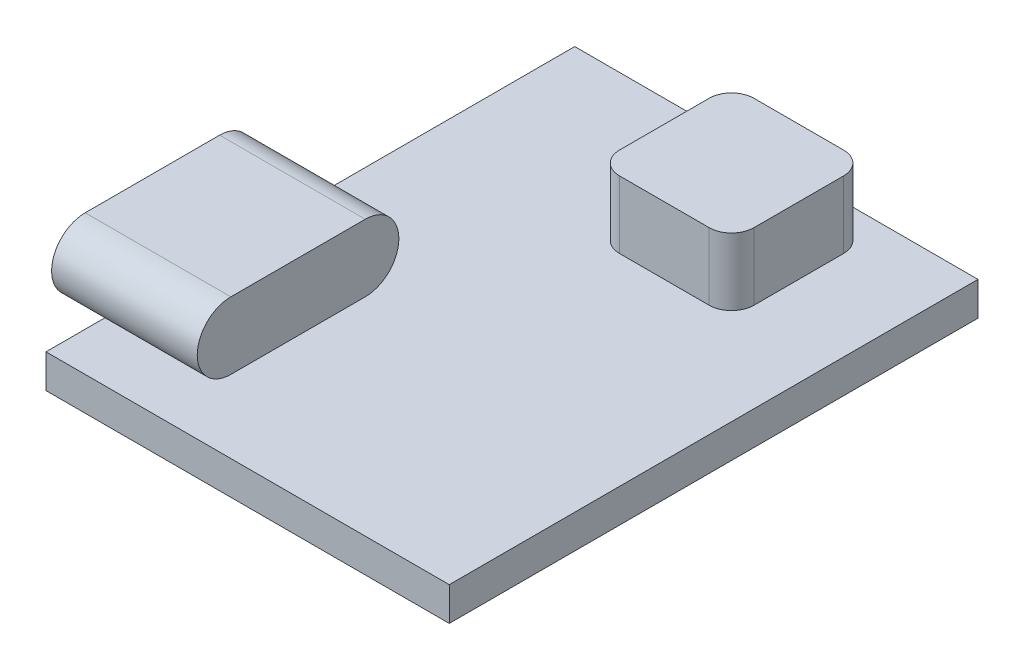
SolidWorks part; units mm, degrees
material "ABS"
ref_plane "Front Plane" through (0, 0, 0) normal (0, 0, 1) x (1, 0, 0)
ref_plane "Top Plane" through (0, 0, 0) normal (0, 1, 0) x (1, 0, 0)
ref_plane "Right Plane" through (0, 0, 0) normal (1, 0, 0) x (0, 0, -1)
sketch "Sketch1" plane through (0, 0, 0) normal (0, 1, 0) x (1, 0, 0)
  line L1 (-9, 11.8) -> (9, 11.8)
  line L2 (-9, 11.8) -> (-9, -11.8)
  line L3 (-9, -11.8) -> (9, -11.8)
  line L4 (9, 11.8) -> (9, -11.8)
  line L5 (0, -11.8) -> (0, 11.8) construction
  line L6 (-9, 0) -> (9, 0) construction
  point P0 (0, 0)
  dimension "D1" = 18
  dimension "D2" = 23.6
extrude "Boss-Extrude1" add sketch "Sketch1" along normal blind 1.5
sketch "Sketch3" plane through (-9, 0, 0) normal (-1, 0, 0) x (0, 0, 1)
  line L0 (2.55, 3) -> (8.55, 3) construction
  line L1 (2.55, 4.5) -> (8.55, 4.5)
  line L2 (2.55, 1.5) -> (8.55, 1.5)
  line L3 (-11.8, 1.5) -> (11.8, 1.5) construction
  line L4 (11.8, 1.5) -> (11.8, 0) construction
  arc A0 (2.55, 4.5) -> (2.55, 1.5) centre (2.55, 3) ccw
  arc A1 (8.55, 1.5) -> (8.55, 4.5) centre (8.55, 3) ccw
  point P2 (5.55, 3)
  point P7 (1.05, 3)
  point P8 (10.05, 3)
  dimension "D1" = 9
  dimension "D2" = 3
  dimension "D3" = 6.25
extrude "Boss-Extrude2" add sketch "Sketch3" along normal blind 1.5 and the other way blind 5 separate body
shell "Shell1" thickness 0.3
sketch "Sketch4" plane through (0, 1.5, 0) normal (0, 1, 0) x (1, 0, 0)
  line L0 (9, 11.8) -> (-9, 11.8) construction
  line L1 (-1, 10.8) -> (5, 10.8)
  line L2 (-1, 10.8) -> (-1, 4.8)
  line L3 (-1, 4.8) -> (5, 4.8)
  line L4 (5, 10.8) -> (5, 4.8)
  line L5 (9, -11.8) -> (9, 11.8) construction
  point P4 (0.5478, 8.1077)
  point P5 (0, 10.6149)
  point P6 (5.2489, 10.0406)
  dimension "D1" = 6
  dimension "D2" = 1
  dimension "D3" = 4
extrude "Boss-Extrude3" add sketch "Sketch4" along normal blind 3 separate body
fillet "Fillet1" radius 1 4 edges at (5, 3, -10.8) (-1, 3, -10.8) (-1, 3, -4.8) (5, 3, -4.8)
